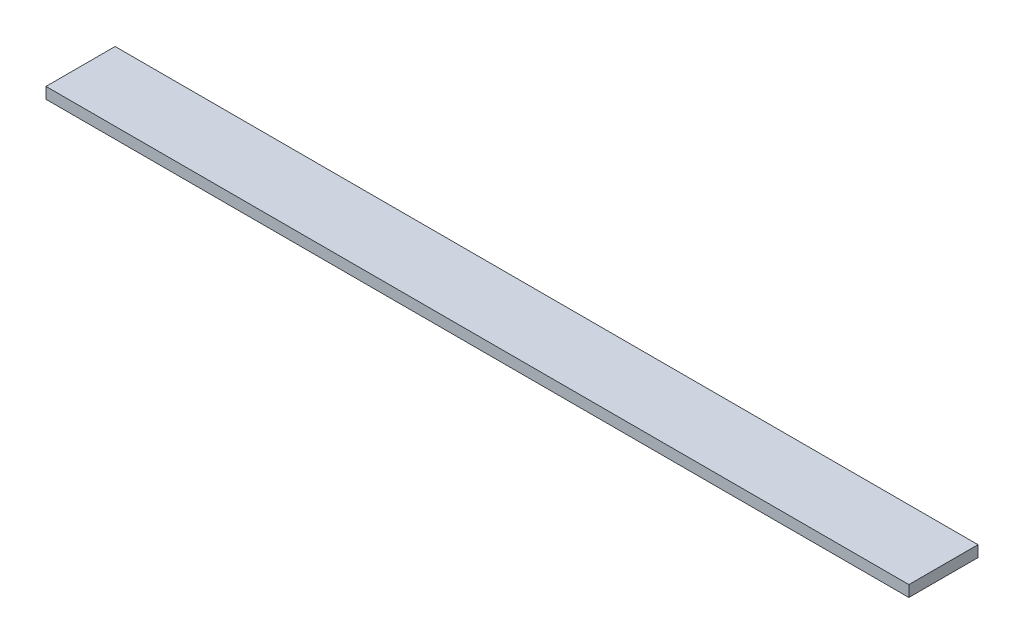
SolidWorks part; units mm, degrees
material "Pine"
ref_plane "Front Plane" through (0, 0, 0) normal (0, 0, 1) x (1, 0, 0)
ref_plane "Top Plane" through (0, 0, 0) normal (0, 1, 0) x (1, 0, 0)
ref_plane "Right Plane" through (0, 0, 0) normal (1, 0, 0) x (0, 0, -1)
sketch "Sketch1" plane through (0, 0, 0) normal (0, 1, 0) x (1, 0, 0)
  line L1 (-721.1739, 422.0587) -> (2212.5261, 422.0587)
  line L2 (-721.1739, 422.0587) -> (-721.1739, 187.1087)
  line L3 (-721.1739, 187.1087) -> (2212.5261, 187.1087)
  line L4 (2212.5261, 422.0587) -> (2212.5261, 187.1087)
  dimension "D1" = 234.95
  dimension "D2" = 2933.7
extrude "Boss-Extrude1" add sketch "Sketch1" along normal blind 38.1 contours L1 L4 L3 L2
